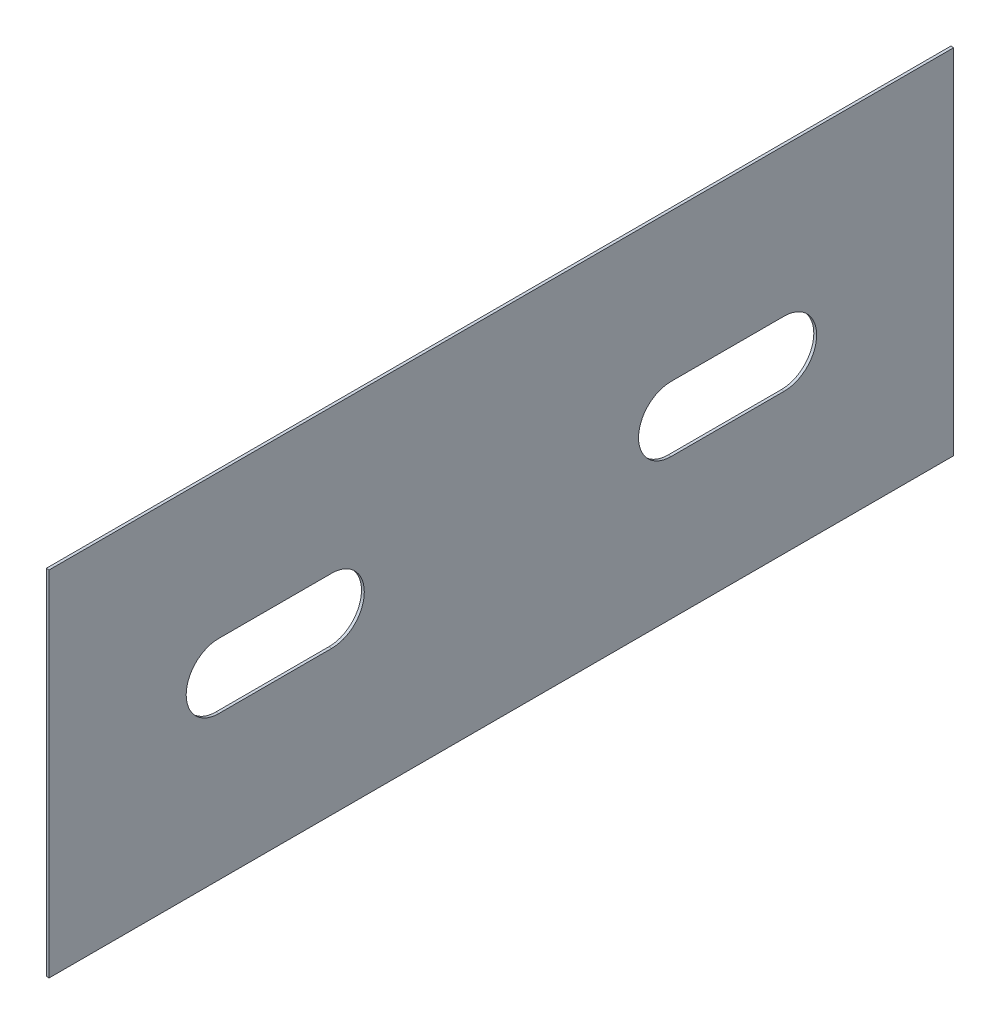
SolidWorks part; units mm, degrees
ref_plane "Front Plane" through (0, 0, 0) normal (0, 0, 1) x (1, 0, 0)
ref_plane "Top Plane" through (0, 0, 0) normal (0, 1, 0) x (1, 0, 0)
ref_plane "Right Plane" through (0, 0, 0) normal (1, 0, 0) x (0, 0, -1)
sketch "Sketch1" plane through (0, 0, 0) normal (1, 0, 0) x (0, 0, -1)
  line L0 (1.2451, 135.7198) -> (1.2451, -114.2802) construction
  line L1 (-318.7549, 135.7198) -> (321.2451, 135.7198)
  line L2 (-318.7549, 135.7198) -> (-318.7549, -114.2802)
  line L3 (-318.7549, -114.2802) -> (321.2451, -114.2802)
  line L4 (321.2451, 135.7198) -> (321.2451, -114.2802)
  line L5 (1.2451, 10.7198) -> (-318.7549, 10.7198) construction
  line L6 (-158.7549, 10.7198) -> (-158.7549, 135.7198) construction
  line L7 (201.2451, 8.1922) -> (121.2451, 8.1922) construction
  line L8 (161.2451, 10.7198) -> (161.2451, 135.7198) construction
  line L9 (-198.7549, 10.7198) -> (-118.7549, 10.7198) construction
  line L10 (-198.7549, 33.7198) -> (-118.7549, 33.7198)
  line L11 (-198.7549, -12.2802) -> (-118.7549, -12.2802)
  line L12 (121.2451, 8.1922) -> (201.2451, 8.1922) construction
  line L13 (121.2451, 31.1922) -> (201.2451, 31.1922)
  line L14 (121.2451, -14.8078) -> (201.2451, -14.8078)
  line L19 (-221.4044, 6.7198) -> (321.2451, 6.7198) construction
  line L20 (-221.4044, 14.7198) -> (321.2451, 14.7198) construction
  arc A0 (-198.7549, 33.7198) -> (-198.7549, -12.2802) centre (-198.7549, 10.7198) ccw
  arc A1 (-118.7549, -12.2802) -> (-118.7549, 33.7198) centre (-118.7549, 10.7198) ccw
  arc A2 (121.2451, 31.1922) -> (121.2451, -14.8078) centre (121.2451, 8.1922) ccw
  arc A3 (201.2451, -14.8078) -> (201.2451, 31.1922) centre (201.2451, 8.1922) ccw
  point P15 (-158.7549, 10.7198)
  point P21 (161.2451, 8.1922)
  dimension "D3" = 40
  dimension "D5" = 23
  dimension "D6" = 23
  dimension "D1" = 640
  dimension "D2" = 250
  dimension "D4" = 40
extrude "Boss-Extrude1" add sketch "Sketch1" along normal blind 2
